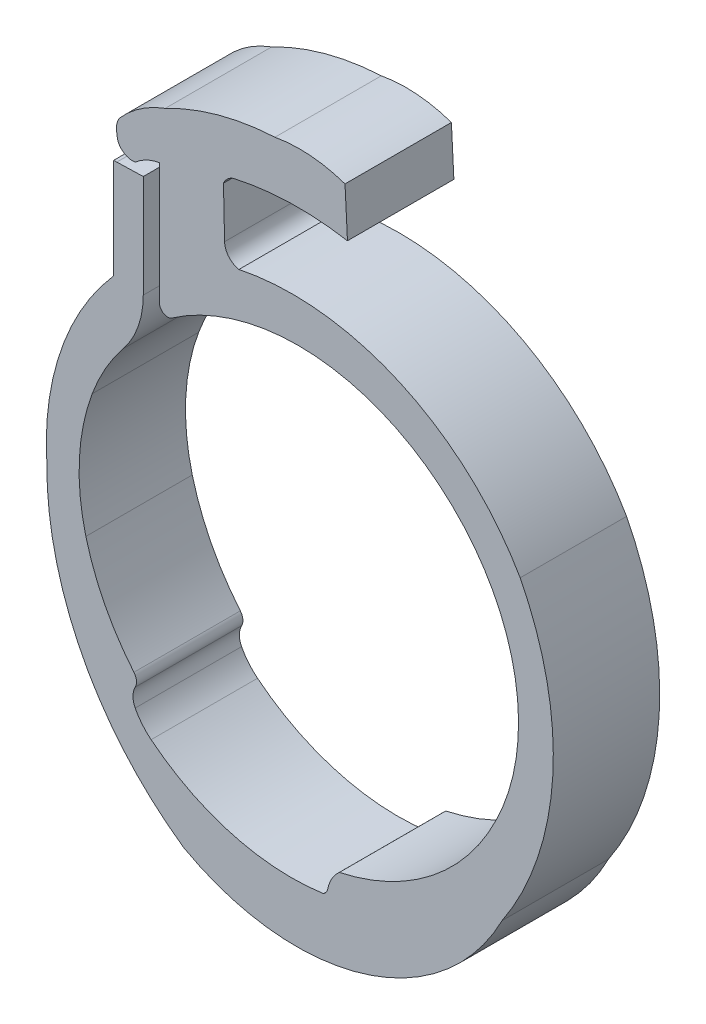
SolidWorks part; units mm, degrees
ref_plane "Front Plane" through (0, 0, 0) normal (0, 0, 1) x (1, 0, 0)
ref_plane "Top Plane" through (0, 0, 0) normal (0, 1, 0) x (1, 0, 0)
ref_plane "Right Plane" through (0, 0, 0) normal (1, 0, 0) x (0, 0, -1)
sketch "Sketch1" plane through (0, 0, 0) normal (0, 0, 1) x (1, 0, 0)
  line L1 (-18.8538, 25.1604) -> (-16.119, 25.2331)
  line L2 (-16.119, 25.2331) -> (-16.119, 14.6133)
  line L3 (-18.8538, 25.1604) -> (-19.1773, 25.155)
  line L4 (-19.1773, 25.155) -> (-19.2173, 14.7602)
  line L5 (-7.8269, 28.7902) -> (-7.7121, 23.6011)
  line L6 (4.7377, 35.0014) -> (4.9925, 30.0351)
  line L7 (-14.4636, 27.3108) -> (-14.4386, 14.6133)
  arc A0 (-26.0868, -5.4347) -> (-19.2173, 14.7602) centre (1.7561, -3.6399) cw
  arc A1 (-26.0868, -5.4347) -> (-11.9486, -32.7584) centre (6.8768, -5.6979) ccw
  arc A2 (-11.9486, -32.7584) -> (20.9685, -22.8537) centre (-0.2874, -11.8627) ccw
  arc A3 (20.9685, -22.8537) -> (22.8486, 8.7896) centre (-4.9745, -5.4348) ccw
  arc A4 (22.8486, 8.7896) -> (-6.2309, 21.8566) centre (-0.6932, -4.7101) ccw
  arc A5 (-7.7121, 23.6011) -> (-6.2309, 21.8566) centre (-5.8968, 23.6413) ccw
  arc A6 (-16.119, 14.6133) -> (-18.1803, 8.8015) centre (-25.3429, 14.6133) cw
  arc A7 (-18.1803, 8.8015) -> (-21.3991, 3.145) centre (-2.7331, -3.7325) ccw
  arc A8 (-21.3991, 3.145) -> (-22.0536, -9.9545) centre (-0.7827, -4.4512) ccw
  arc A9 (-22.0536, -9.9545) -> (-17.0854, -19.6369) centre (1.9885, -3.7342) ccw
  arc A10 (-17.0854, -19.6369) -> (-16.9516, -20.9027) centre (-17.9645, -20.3698) cw
  arc A11 (-16.9516, -20.9027) -> (-16.9555, -22.776) centre (-15.1642, -21.8431) ccw
  arc A12 (-16.9555, -22.776) -> (-15.3079, -24.7835) centre (-11.3542, -19.8589) ccw
  arc A13 (-13.2853, 13.9659) -> (17.0132, 10.4943) centre (-0.096, -4.8755) cw
  arc A14 (-14.4386, 14.6133) -> (-13.2853, 13.9659) centre (-13.5828, 14.7869) ccw
  arc A15 (17.0132, 10.4943) -> (20.3257, -14.2198) centre (0.5551, -4.2906) cw
  arc A16 (20.3257, -14.2198) -> (4.1515, -26.9386) centre (-0.8098, -3.9859) cw
  arc A17 (-15.3079, -24.7835) -> (2.5142, -29.6563) centre (-0.7849, -6.6942) ccw
  arc A18 (2.5142, -29.6563) -> (2.9549, -28.9969) centre (1.9114, -28.7764) ccw
  arc A19 (2.9549, -28.9969) -> (4.1515, -26.9386) centre (6.6766, -29.7835) cw
  arc A20 (-7.8269, 28.7902) -> (-6.7924, 29.7301) centre (-6.2533, 28.0975) cw
  arc A21 (-2.5082, 35.558) -> (-13.8483, 32.4736) centre (-1.1176, 8.0569) ccw
  arc A22 (-13.8483, 32.4736) -> (-18.5735, 29.2425) centre (-9.8595, 21.5695) ccw
  arc A23 (-2.5082, 35.558) -> (4.7377, 35.0014) centre (0.0616, 21.5701) cw
  arc A24 (-18.5735, 29.2425) -> (-18.8312, 27.67) centre (-16.9216, 28.1644) ccw
  arc A25 (-18.8312, 27.67) -> (-16.9216, 26.1229) centre (-17.2563, 27.6618) ccw
  arc A26 (-16.9216, 26.1229) -> (-14.4636, 27.3108) centre (-13.5292, 22.2403) cw
  arc A27 (-6.7924, 29.7301) -> (4.9925, 30.0351) centre (-0.1392, 0.4859) cw
  dimension "D1" = 27.1378
  dimension "D2" = 19.8927
  dimension "D3" = 1.1445
  dimension "D4" = 2.0197
  dimension "D5" = 0.8732
  dimension "D6" = 23.4828
  dimension "D7" = 1.9726
  dimension "D8" = 1.5749
  dimension "D9" = 5.1559
  dimension "D10" = 6.3154
  dimension "D11" = 22.9991
  dimension "D12" = 1.0666
extrude "Boss-Extrude1" add sketch "Sketch1" along normal blind 11
